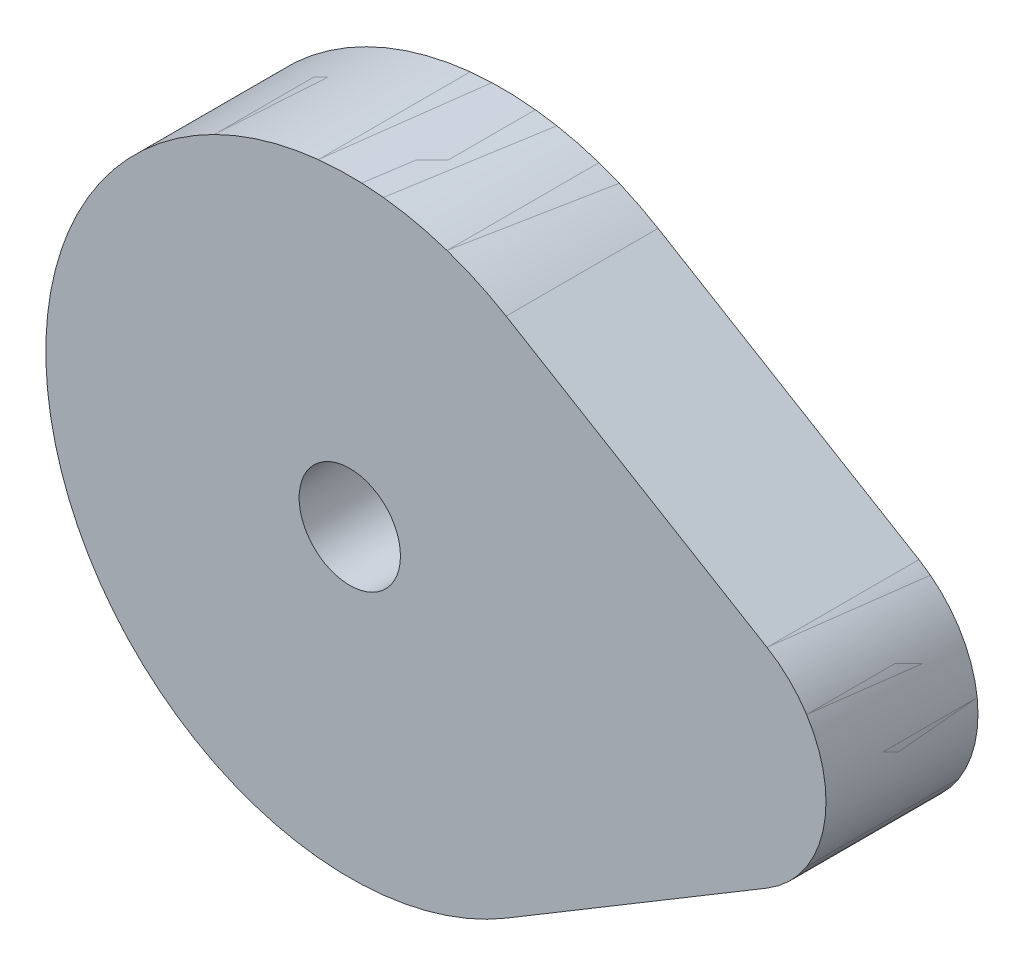
SolidWorks part; units mm, degrees
ref_plane "Alzado" through (0, 0, 0) normal (0, 0, 1) x (1, 0, 0)
ref_plane "Planta" through (0, 0, 0) normal (0, 1, 0) x (1, 0, 0)
ref_plane "Vista lateral" through (0, 0, 0) normal (1, 0, 0) x (0, 0, -1)
sketch "Croquis1" plane through (0, 0, 0) normal (0, 0, 1) x (1, 0, 0)
  line L0 (41.1714, -10.2914) -> (15.4286, -25.7286)
  line L1 (41.1714, 10.2914) -> (15.4286, 25.7286)
  arc A0 (15.4286, 25.7286) -> (15.4286, -25.7286) centre (0, 0) ccw
  arc A1 (41.1714, -10.2914) -> (41.1714, 10.2914) centre (35, 0) ccw
  circle A2 centre (0, 0) radius 5
  dimension "D1" = 35
  dimension "D2" = 24
  dimension "D3" = 60
  dimension "D4" = 10
extrude "Saliente-Extruir1" add sketch "Croquis1" along normal blind 15
sketch "Croquis2" plane through (0, 0, 15) normal (0, 0, 1) x (1, 0, 0)
  line L0 (15.4286, -25.7286) -> (41.1714, -10.2914) construction
  line L1 (41.1714, 10.2914) -> (15.4286, 25.7286) construction
  line L2 (15.4286, -25.7286) -> (41.1714, -10.2914)
  line L3 (41.1714, 10.2914) -> (15.4286, 25.7286)
  arc A0 (41.1714, -10.2914) -> (41.1714, 10.2914) centre (35, 0) ccw construction
  arc A1 (15.4286, 25.7286) -> (15.4286, -25.7286) centre (0, 0) ccw construction
  arc A2 (41.1714, -10.2914) -> (41.1714, 10.2914) centre (35, 0) ccw
  arc A3 (15.4286, 25.7286) -> (15.4286, -25.7286) centre (0, 0) ccw
surface "Superficie-Extruir2" sketch "Croquis2" parameters "D1"=15
